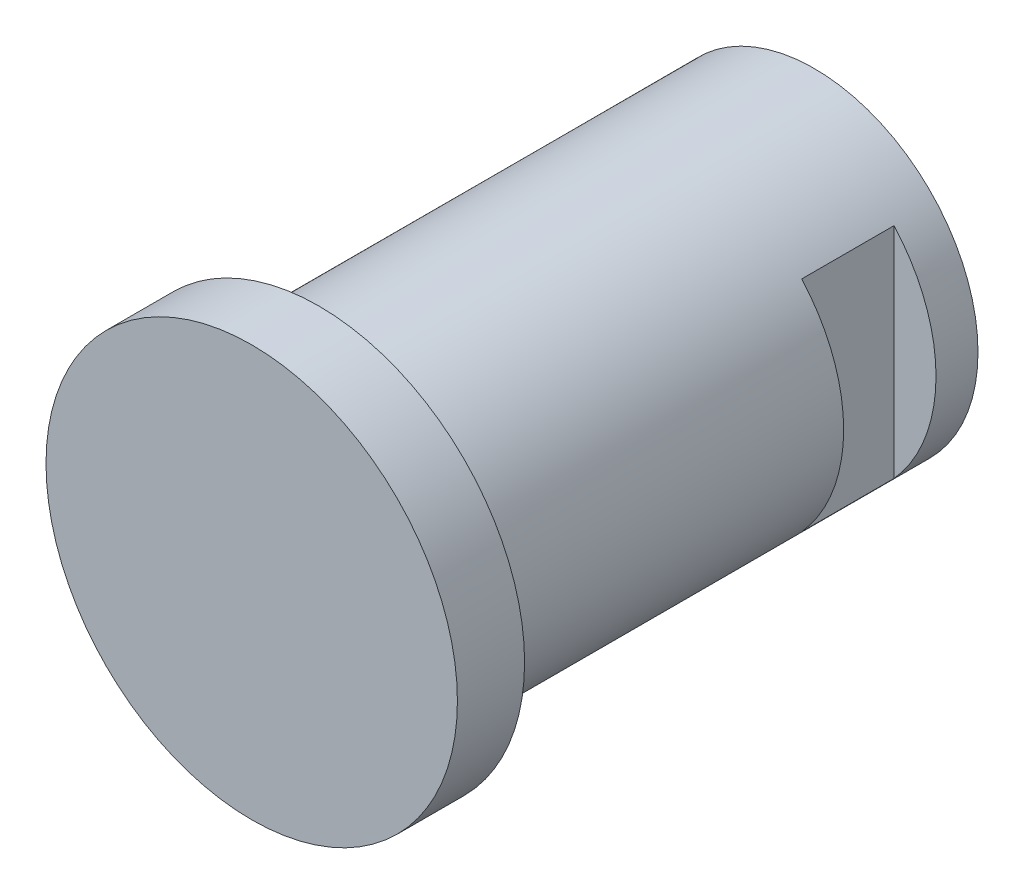
SolidWorks part; units mm, degrees
ref_plane "Front Plane" through (0, 0, 0) normal (0, 0, 1) x (1, 0, 0)
ref_plane "Top Plane" through (0, 0, 0) normal (0, 1, 0) x (1, 0, 0)
ref_plane "Right Plane" through (0, 0, 0) normal (1, 0, 0) x (0, 0, -1)
sketch "Sketch1" plane through (0, 0, 0) normal (0, 0, 1) x (1, 0, 0)
  circle A0 centre (0, 0) radius 4.953
  dimension "D1" = 9.906
extrude "Boss-Extrude1" add sketch "Sketch1" along normal blind 17.018
sketch "Sketch2" plane through (0, 0, 17.018) normal (0, 0, 1) x (1, 0, 0)
  circle A0 centre (0, 0) radius 6.223
  circle A1 centre (0, 0) radius 4.953 construction
  dimension "D1" = 1.27
extrude "Boss-Extrude2" add sketch "Sketch2" against normal blind 2.032
sketch "Sketch3" plane through (0, 0, 0) normal (0, 1, 0) x (1, 0, 0)
  line L0 (-4.953, 0) -> (-4.953, -14.986) construction
  line L1 (-4.953, -1.27) -> (4.953, -1.27)
  line L2 (-4.953, -1.27) -> (-4.953, -4.064)
  line L3 (-4.953, -4.064) -> (4.953, -4.064)
  line L4 (4.953, -1.27) -> (4.953, -4.064)
  line L5 (4.953, -14.986) -> (4.953, 0) construction
  line L6 (4.953, 0) -> (-4.953, 0) construction
  line L7 (-3.683, -1.27) -> (3.683, -1.27)
  line L8 (-3.683, -1.27) -> (-3.683, -4.064)
  line L9 (-3.683, -4.064) -> (3.683, -4.064)
  line L10 (3.683, -1.27) -> (3.683, -4.064)
  dimension "D1" = 1.27
  dimension "D2" = 2.794
  dimension "D3" = 1.27
  dimension "D4" = 1.27
extrude "Cut-Extrude1" cut sketch "Sketch3" against normal through all and the other way through all contours L1 L10 L3 L4 | L8 L1 L2 L3
